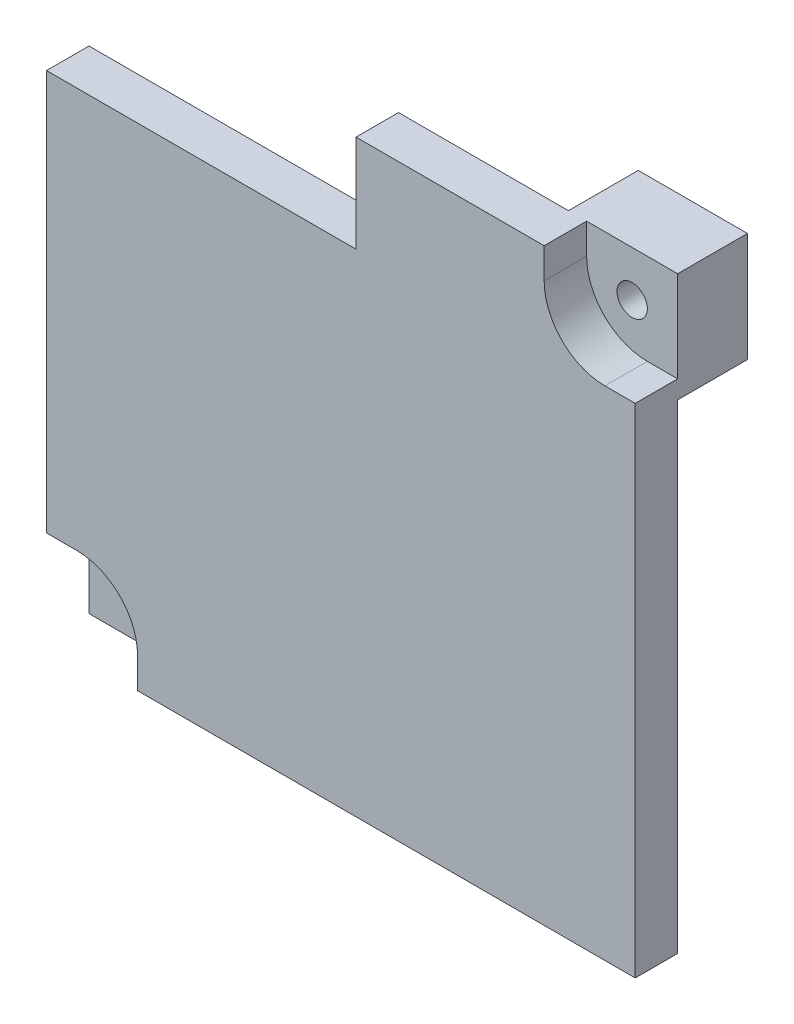
SolidWorks part; units mm, degrees
ref_plane "Front Plane" through (0, 0, 0) normal (0, 0, 1) x (1, 0, 0)
ref_plane "Top Plane" through (0, 0, 0) normal (0, 1, 0) x (1, 0, 0)
ref_plane "Right Plane" through (0, 0, 0) normal (1, 0, 0) x (0, 0, -1)
sketch "Sketch1" plane through (0, 0, 0) normal (0, 0, 1) x (1, 0, 0)
  line L1 (9.7, -9.7) -> (-6.7, -9.7)
  line L2 (9.7, -9.7) -> (9.7, 6.7)
  line L3 (6.7, 9.7) -> (-9.7, 9.7)
  line L4 (-9.7, -6.7) -> (-9.7, 9.7)
  line L5 (9.7, -9.7) -> (-9.7, 9.7) construction
  line L6 (9.7, 9.7) -> (-9.7, -9.7) construction
  line L9 (-9.7, -6.7) -> (-8.7, -6.7)
  line L10 (-6.7, -9.7) -> (-6.7, -8.7)
  line L13 (9.7, 6.7) -> (8.7, 6.7)
  line L14 (6.7, 9.7) -> (6.7, 8.7)
  line L15 (-9.7, 9.7) -> (0.5, 9.7)
  line L16 (-9.7, 9.7) -> (-9.7, 6.5)
  line L17 (-9.7, 6.5) -> (0.5, 6.5)
  line L18 (0.5, 9.7) -> (0.5, 6.5)
  arc A0 (8.7, 6.7) -> (6.7, 8.7) centre (8.7, 8.7) cw
  arc A1 (-6.7, -8.7) -> (-8.7, -6.7) centre (-8.7, -8.7) ccw
  point P0 (0, 0)
  point P14 (6.7, 6.7)
  point P17 (-6.7, -6.7)
  dimension "D5" = 2
  dimension "D1" = 19.4
  dimension "D2" = 19.4
  dimension "D3" = 3
  dimension "D4" = 3
  dimension "D6" = 10.2
  dimension "D7" = 3.2
extrude "Boss-Extrude2" add sketch "Sketch1" along normal blind 1.4 contours A1 L10 L1 L2 L13 A0 L14 L3 L18 L17 L4 L9
sketch "Sketch2" plane through (0, 0, 0) normal (0, 0, -1) x (-1, 0, 0)
  line L0 (-9.7, -9.7) -> (-9.7, 6.7) construction
  line L1 (-9.7, 6.1) -> (-6.1, 6.1)
  line L2 (-9.7, 6.1) -> (-9.7, 9.7)
  line L3 (-9.7, 9.7) -> (-6.1, 9.7)
  line L4 (-6.1, 6.1) -> (-6.1, 9.7)
  line L5 (-6.7, 9.7) -> (-0.5, 9.7) construction
  line L6 (-9.7, -9.7) -> (6.7, -9.7) construction
  line L7 (0.2, -9.7) -> (9.7, -9.7)
  line L8 (0.2, -9.7) -> (0.2, -0.2)
  line L9 (0.2, -0.2) -> (9.7, -0.2)
  line L10 (9.7, -9.7) -> (9.7, -0.2)
  line L11 (9.7, -6.7) -> (9.7, 6.5) construction
  dimension "D1" = 3.6
  dimension "D2" = 3.6
  dimension "D3" = 9.5
  dimension "D4" = 9.5
extrude "Boss-Extrude3" add sketch "Sketch2" along normal blind 2.3
sketch "Sketch4" plane through (0, 0, 0) normal (0, 0, 1) x (1, 0, 0)
  line L0 (8.2, 9.7) -> (8.2, 8.2) construction
  line L1 (6.7, 9.7) -> (9.7, 9.7) construction
  line L2 (-9.7, -8.2) -> (-8.2, -8.2) construction
  line L3 (-9.7, -9.7) -> (-9.7, -6.7) construction
  circle A0 centre (8.2, 8.2) radius 0.5
  circle A1 centre (-8.2, -8.2) radius 0.5
  dimension "D1" = 1
  dimension "D2" = 1
extrude "Cut-Extrude1" cut sketch "Sketch4" against normal through all both and the other way through all
